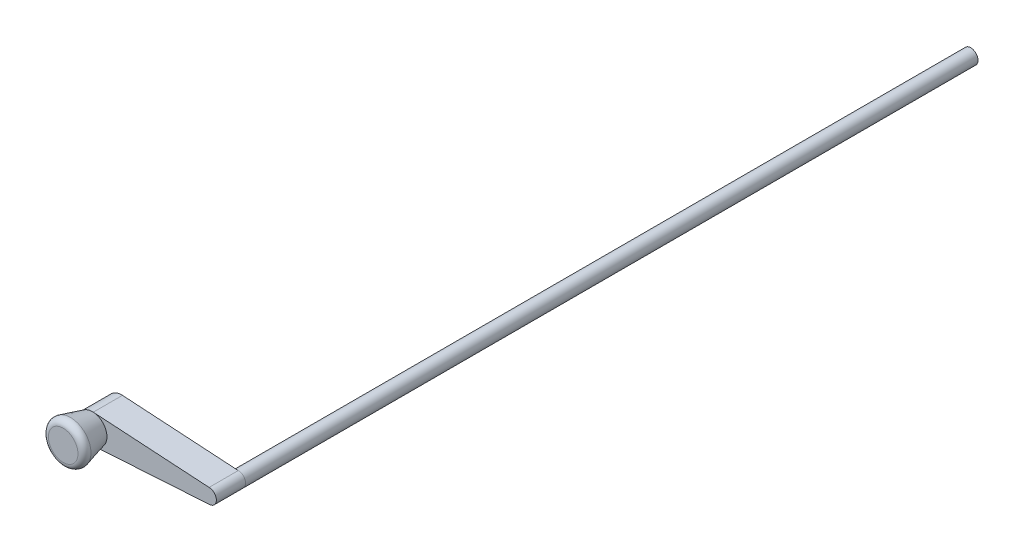
SolidWorks part; units mm, degrees
ref_plane "Front Plane" through (0, 0, 0) normal (0, 0, 1) x (1, 0, 0)
ref_plane "Top Plane" through (0, 0, 0) normal (0, 1, 0) x (1, 0, 0)
ref_plane "Right Plane" through (0, 0, 0) normal (1, 0, 0) x (0, 0, -1)
sketch "Sketch1" plane through (0, 0, 0) normal (0, 0, 1) x (1, 0, 0)
  circle A0 centre (0, 0) radius 3.175
  dimension "D1" = 6.35
extrude "Boss-Extrude1" add sketch "Sketch1" along normal blind 38.1 and the other way blind 312.42
ref_plane "Plane1" through (0, 3.175, 0) normal (0, 1, 0) x (1, 0, 0)
sketch "Sketch5" plane through (0, 0, 38.1) normal (0, 0, 1) x (1, 0, 0)
  line L0 (0, -3.1812) -> (0, 3.1812) construction
  line L1 (0, -3.1812) -> (-50.4031, -6.3376)
  line L2 (-50.4031, 6.3376) -> (0, 3.1812)
  circle A0 centre (-50.8, 0) radius 6.35 construction
  circle A2 centre (0, 0) radius 3.175 construction
  arc A3 (0, 3.1812) -> (0, -3.1812) centre (0, 0) cw
  arc A4 (-50.4031, -6.3376) -> (-50.4031, 6.3376) centre (-50.8, 0) cw
  point P5 (0, 0)
  dimension "D1" = 6.35
  dimension "D2" = 50.8
extrude "Boss-Extrude2" add sketch "Sketch5" along normal blind 12.7
sketch "Sketch6" plane through (0, 0, 50.8) normal (0, 0, 1) x (1, 0, 0)
  circle A0 centre (-50.8, 0) radius 6.35 construction
  circle A1 centre (-50.8, 0) radius 6.35
extrude "Boss-Extrude3" add sketch "Sketch6" along normal blind 12.7 draft 15 draft outward yes
sketch "Sketch7" plane through (0, 0, -312.42) normal (0, 0, -1) x (-1, 0, 0)
  circle A0 centre (0, 0) radius 26.162
  dimension "D1" = 52.324
extrude "Cut-Extrude1" cut sketch "Sketch7" against normal blind 31.75
fillet "Fillet1" radius 2.54 1 edges at (-41.047, 0, 63.5)
